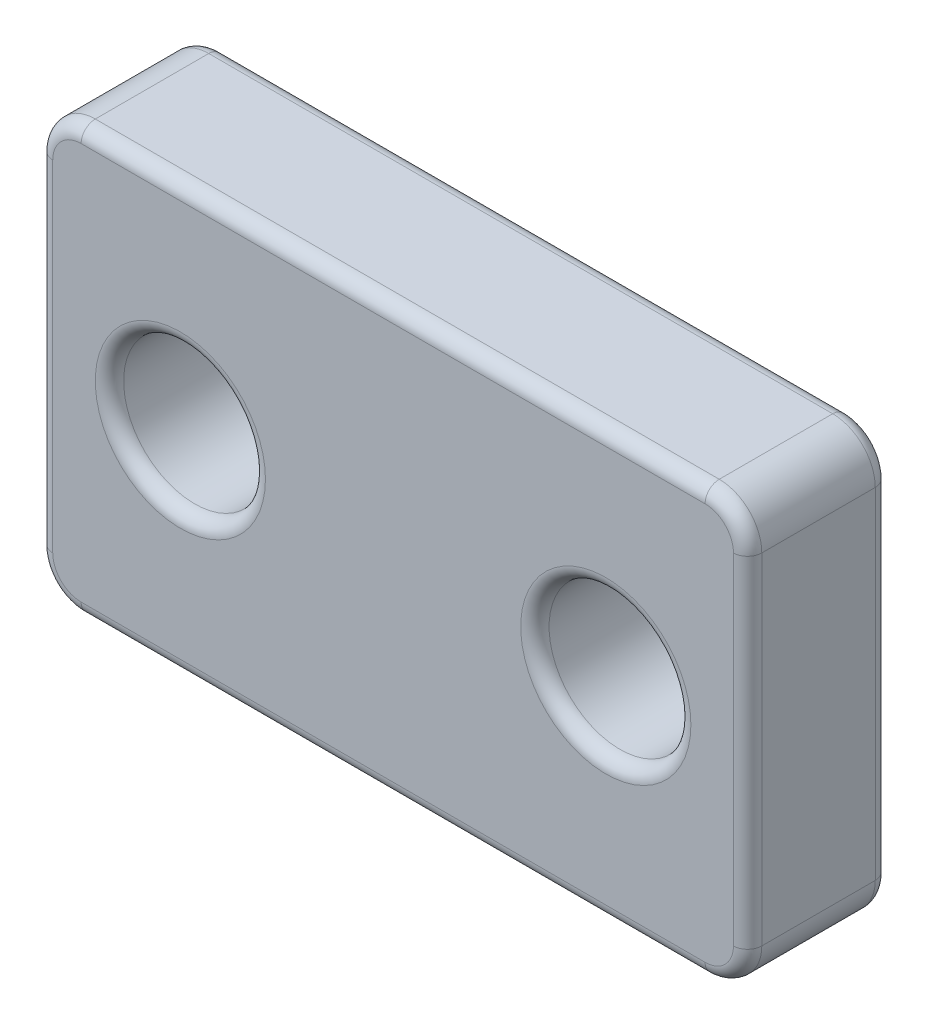
SolidWorks part; units mm, degrees
ref_plane "Front Plane" through (0, 0, 0) normal (0, 0, 1) x (1, 0, 0)
ref_plane "Top Plane" through (0, 0, 0) normal (0, 1, 0) x (1, 0, 0)
ref_plane "Right Plane" through (0, 0, 0) normal (1, 0, 0) x (0, 0, -1)
sketch "Sketch1" plane through (0, 0, 0) normal (0, 0, 1) x (1, 0, 0)
  line L1 (25, -15) -> (-25, -15)
  line L2 (25, -15) -> (25, 15)
  line L3 (25, 15) -> (-25, 15)
  line L4 (-25, -15) -> (-25, 15)
  line L5 (25, -15) -> (-25, 15) construction
  line L6 (25, 15) -> (-25, -15) construction
  point P0 (0, 0)
  dimension "D1" = 50
  dimension "D2" = 30
extrude "Boss-Extrude1" add sketch "Sketch1" along normal blind 10
sketch "Sketch2" plane through (0, 0, 10) normal (0, 0, 1) x (1, 0, 0)
  line L0 (-33.2844, 0) -> (33.3352, 0) construction
  circle A0 centre (-15, 0) radius 5
  circle A1 centre (15, 0) radius 5
  dimension "D1" = 10
  dimension "D2" = 10
  dimension "D3" = 15
  dimension "D4" = 15
extrude "Cut-Extrude1" cut sketch "Sketch2" against normal blind 10
fillet "Fillet1" radius 3 4 edges at (-25, -15, 5) (25, -15, 5) (-25, 15, 5) (25, 15, 5)
fillet "Fillet2" radius 1 20 edges at (-24.1213, 14.1213, 0) (0, 15, 0) (24.1213, 14.1213, 0) (25, 0, 0) (24.1213, -14.1213, 0) (0, -15, 0) (-24.1213, -14.1213, 0) (24.1213, 14.1213, 10) (25, 0, 10) (24.1213, -14.1213, 10) (0, -15, 10) (-24.1213, -14.1213, 10) (-25, 0, 10) (-24.1213, 14.1213, 10) (20, 0, 10) (20, 0, 0) (-10, 0, 10) (-10, 0, 0) (-25, 0, 0) (0, 15, 10)
